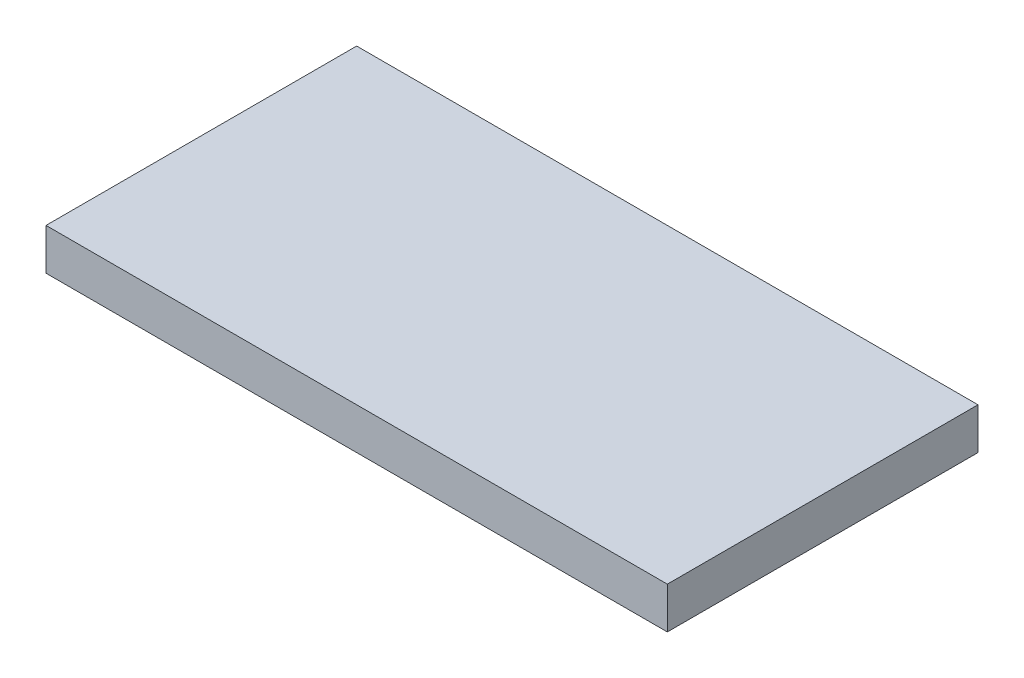
SolidWorks part; units mm, degrees
ref_plane "Front Plane" through (0, 0, 0) normal (0, 0, 1) x (1, 0, 0)
ref_plane "Top Plane" through (0, 0, 0) normal (0, 1, 0) x (1, 0, 0)
ref_plane "Right Plane" through (0, 0, 0) normal (1, 0, 0) x (0, 0, -1)
sketch "Sketch1" plane through (0, 0, 0) normal (0, 1, 0) x (1, 0, 0)
  line L1 (0, 0) -> (192, 0)
  line L2 (0, 0) -> (0, 96)
  line L3 (0, 96) -> (192, 96)
  line L4 (192, 0) -> (192, 96)
  dimension "D1" = 192
  dimension "D2" = 96
extrude "Boss-Extrude1" add sketch "Sketch1" along normal blind 12.8
sketch "Sketch2" plane through (0, 0, 0) normal (0, -1, 0) x (1, 0, 0)
  line L0 (192, 0) -> (192, -96) construction
  line L1 (179.5, -12.5) -> (12.5, -12.5)
  line L2 (179.5, -12.5) -> (179.5, -83.5)
  line L3 (179.5, -83.5) -> (12.5, -83.5)
  line L4 (12.5, -12.5) -> (12.5, -83.5)
  line L5 (0, 0) -> (192, 0) construction
  line L6 (192, -96) -> (0, -96) construction
  line L7 (0, -96) -> (0, 0) construction
  dimension "D1" = 12.5
  dimension "D2" = 12.5
  dimension "D3" = 12.5
  dimension "D4" = 12.5
extrude "Cut-Extrude1" cut sketch "Sketch2" against normal blind 9.2
hole_wizard "M3 Clearance Hole1" positions "Sketch3" profile "Sketch5" hole size "M3" standard "ANSI Metric"
sketch "Sketch3" plane through (0, 0, 0) normal (0, -1, 0) x (-1, 0, 0)
  line L0 (0, 0) -> (-192, 0) construction
  line L1 (0, 96) -> (0, 0) construction
  line L2 (-192, 96) -> (0, 96) construction
  line L3 (-192, 0) -> (-192, 96) construction
  point P0 (-13, 9.1)
  point P2 (-96, 9.1)
  point P4 (-179, 9.1)
  point P6 (-179, 86.9)
  point P8 (-96, 86.9)
  point P10 (-13, 86.9)
  dimension "D1" = 9.1
  dimension "D2" = 13
  dimension "D3" = 13
  dimension "D4" = 9.1
  dimension "D5" = 9.1
  dimension "D6" = 9.1
  dimension "D7" = 9.1
  dimension "D8" = 9.1
  dimension "D9" = 13
  dimension "D10" = 13
  dimension "D11" = 96
  dimension "D12" = 96
sketch "Sketch5" plane through (13, 0, -9.1) normal (1, 0, 0) x (0, 0, -1)
  line L0 (0, 0) -> (0, 6.0215)
  line L1 (0, 6.0215) -> (1.7, 5)
  line L2 (1.7, 5) -> (1.7, 0)
  line L5 (1.7, 0) -> (0, 0)
  line L10 (0, 6.0215) -> (-1.7, 5) construction
  line L11 (0, -6.35) -> (0, 107.95) construction
  dimension "Hole Dia." = 3.4
  dimension "Hole Depth" = 5
  dimension "Drill Angle" = 118
sketch "Sketch6" plane through (0, 9.2, 0) normal (0, -1, 0) x (1, 0, 0)
  line L0 (0, -96) -> (0, 0) construction
  line L1 (16.5, -33.9) -> (25.1, -33.9)
  line L2 (16.5, -33.9) -> (16.5, -61.7)
  line L3 (16.5, -61.7) -> (25.1, -61.7)
  line L4 (25.1, -33.9) -> (25.1, -61.7)
  line L5 (192, 0) -> (192, -96) construction
  line L6 (175.5, -33.9) -> (166.9, -33.9)
  line L7 (175.5, -33.9) -> (175.5, -61.7)
  line L8 (175.5, -61.7) -> (166.9, -61.7)
  line L9 (166.9, -33.9) -> (166.9, -61.7)
  line L10 (0, 0) -> (192, 0) construction
  dimension "D1" = 8.6
  dimension "D2" = 27.8
  dimension "D3" = 25.1
  dimension "D4" = 27.8
  dimension "D5" = 8.6
  dimension "D6" = 25.1
  dimension "D7" = 61.7
  dimension "D8" = 61.7
extrude "Boss-Extrude2" add sketch "Sketch6" along normal blind 9.6
sketch "Sketch7" plane through (0, 9.2, 0) normal (0, -1, 0) x (1, 0, 0)
  line L0 (0, 0) -> (192, 0) construction
  line L1 (106.1, -39.3) -> (122, -39.3)
  line L2 (106.1, -39.3) -> (106.1, -46.9)
  line L3 (106.1, -46.9) -> (122, -46.9)
  line L4 (122, -39.3) -> (122, -46.9)
  line L5 (192, 0) -> (192, -96) construction
  dimension "D1" = 15.9
  dimension "D2" = 7.6
  dimension "D3" = 39.3
  dimension "D4" = 70
extrude "Boss-Extrude3" add sketch "Sketch7" along normal blind 11.2
